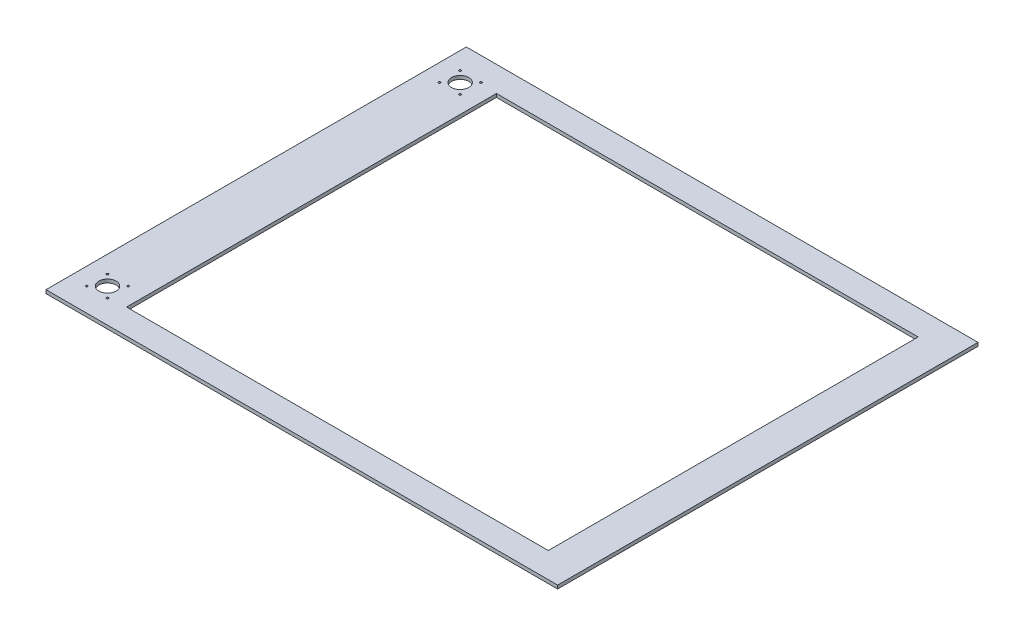
SolidWorks part; units mm, degrees
ref_plane "Front Plane" through (0, 0, 0) normal (0, 0, 1) x (1, 0, 0)
ref_plane "Top Plane" through (0, 0, 0) normal (0, 1, 0) x (1, 0, 0)
ref_plane "Right Plane" through (0, 0, 0) normal (1, 0, 0) x (0, 0, -1)
sketch "Sketch1" plane through (0, 0, 0) normal (0, 1, 0) x (1, 0, 0)
  line L1 (0, 0) -> (740, 0)
  line L2 (0, 0) -> (0, 608)
  line L3 (0, 608) -> (740, 608)
  line L4 (740, 0) -> (740, 608)
  line L5 (80, 36.5) -> (690, 36.5)
  line L6 (80, 36.5) -> (80, 571.5)
  line L7 (80, 571.5) -> (690, 571.5)
  line L8 (690, 36.5) -> (690, 571.5)
  circle A0 centre (40, 559) radius 12.5
  circle A1 centre (40, 49) radius 12.5
  circle A2 centre (25, 64) radius 1.5
  circle A3 centre (25, 34) radius 1.5
  circle A4 centre (55, 34) radius 1.5
  circle A5 centre (55, 64) radius 1.5
  circle A6 centre (25, 574) radius 1.5
  circle A7 centre (55, 574) radius 1.5
  circle A8 centre (55, 544) radius 1.5
  circle A9 centre (25, 544) radius 1.5
  dimension "D9" = 25
  dimension "D10" = 40
  dimension "D12" = 25
  dimension "D13" = 40
  dimension "D15" = 3
  dimension "D16" = 3
  dimension "D17" = 3
  dimension "D18" = 3
  dimension "D27" = 3
  dimension "D28" = 3
  dimension "D29" = 3
  dimension "D30" = 3
  dimension "D1" = 740
  dimension "D2" = 608
  dimension "D3" = 610
  dimension "D4" = 535
  dimension "D5" = 36.5
  dimension "D6" = 36.5
  dimension "D7" = 80
  dimension "D8" = 50
  dimension "D11" = 12.5
  dimension "D14" = 12.5
  dimension "D19" = 30
  dimension "D20" = 30
  dimension "D21" = 30
  dimension "D22" = 30
  dimension "D23" = 15
  dimension "D24" = 15
  dimension "D25" = 15
  dimension "D26" = 15
  dimension "D31" = 15
  dimension "D32" = 15
  dimension "D33" = 30
  dimension "D34" = 30
  dimension "D35" = 30
  dimension "D36" = 30
  dimension "D37" = 15
  dimension "D38" = 15
other "AlignGroup1"
extrude "Boss-Extrude1" add sketch "Sketch1" along normal blind 5
